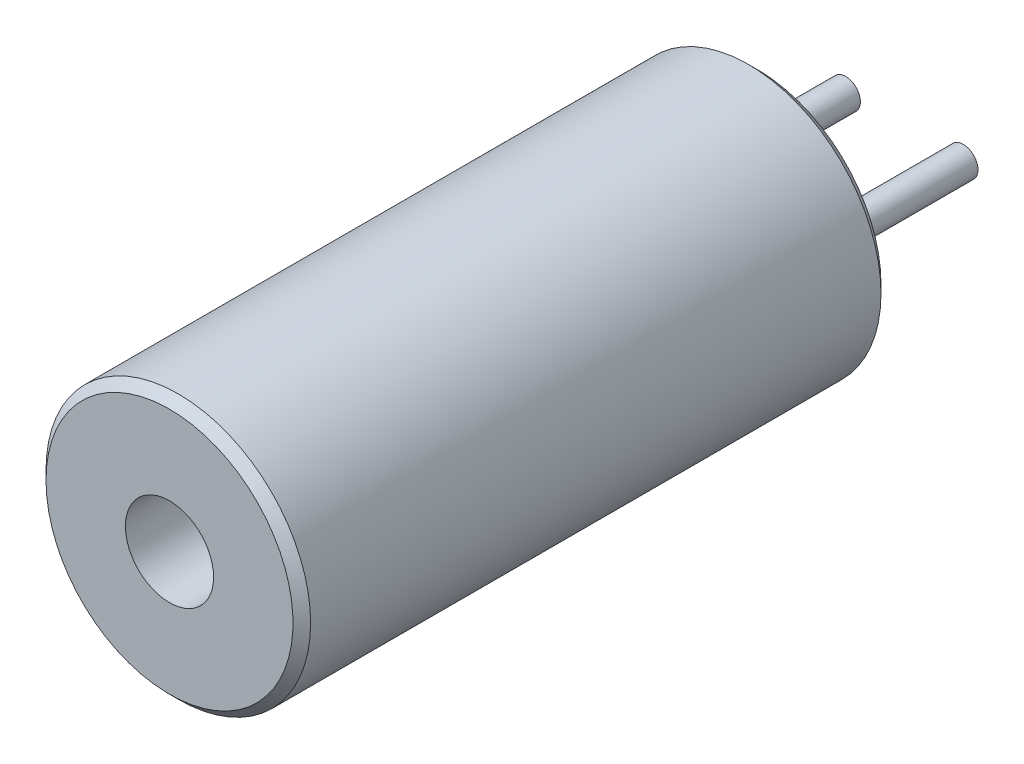
SolidWorks part; units mm, degrees
ref_plane "Front Plane" through (0, 0, 0) normal (0, 0, 1) x (1, 0, 0)
ref_plane "Top Plane" through (0, 0, 0) normal (0, 1, 0) x (1, 0, 0)
ref_plane "Right Plane" through (0, 0, 0) normal (1, 0, 0) x (0, 0, -1)
sketch "Sketch1" plane through (0, 0, 0) normal (1, 0, 0) x (0, 0, -1)
  line L0 (-10, 0) -> (10, 0) construction
  line L1 (-10, 0) -> (-10, 4.5)
  line L2 (-10, 4.5) -> (10, 4.5)
  line L3 (10, 4.5) -> (10, 0)
  line L4 (-10, 0) -> (10, 0)
  dimension "D1" = 20
  dimension "D2" = 9
revolve "Revolve1" add sketch "Sketch1" angle 360 about L0
sketch "Sketch2" plane through (0, 0, 10) normal (0, 0, 1) x (1, 0, 0)
  circle A0 centre (0, 0) radius 1.5
  dimension "D1" = 3
extrude "Cut-Extrude1" cut sketch "Sketch2" against normal blind 3
chamfer "Chamfer1" distance 0.3 angle 45 2 edges at (4.5, 0, 10) (4.5, 0, -10)
sketch "Sketch3" plane through (0, 0, -10) normal (0, 0, -1) x (-1, 0, 0)
  line L0 (-2, 0) -> (2, 0) construction
  circle A0 centre (-2, 0) radius 0.5
  circle A1 centre (2, 0) radius 0.5
  point P6 (2.227, 0)
  dimension "D2" = 1
  dimension "D1" = 4
extrude "Boss-Extrude1" add sketch "Sketch3" along normal blind 5
